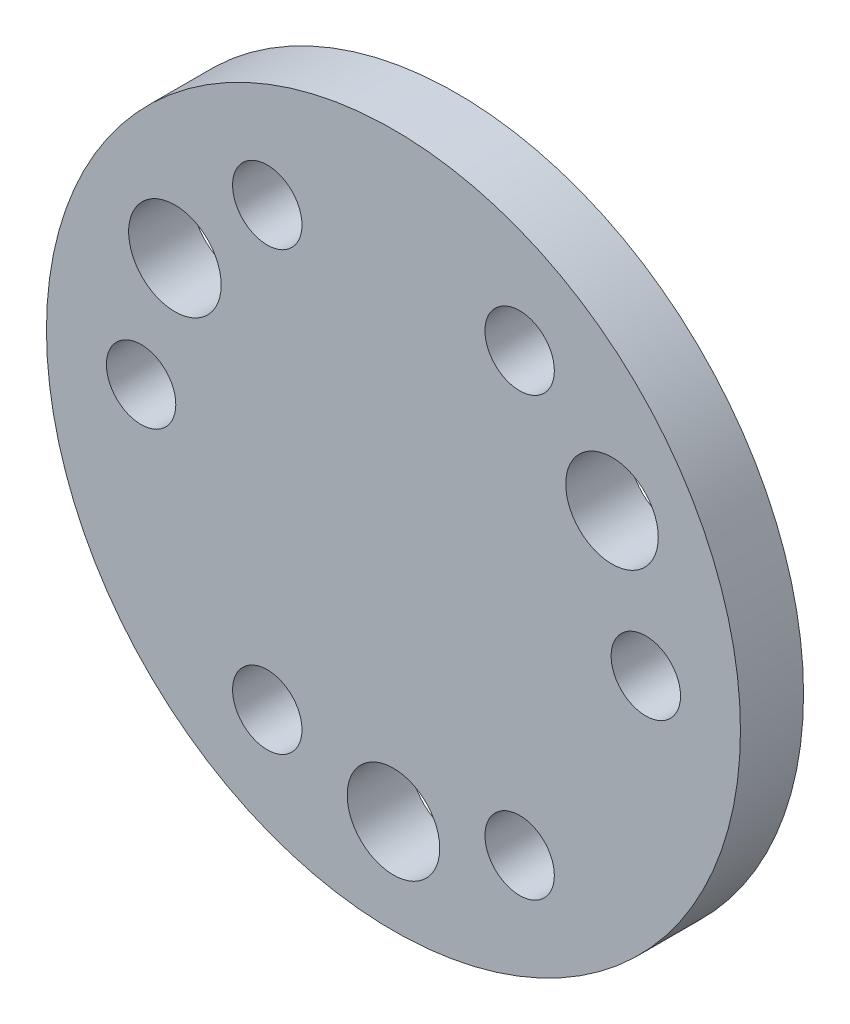
SolidWorks part; units mm, degrees
ref_plane "前视基准面" through (0, 0, 0) normal (0, 0, 1) x (1, 0, 0)
ref_plane "上视基准面" through (0, 0, 0) normal (0, 1, 0) x (1, 0, 0)
ref_plane "右视基准面" through (0, 0, 0) normal (1, 0, 0) x (0, 0, -1)
other "Configuration Table"
sketch "草图2" plane through (0, 0, 0) normal (0, 0, 1) x (1, 0, 0)
  circle A0 centre (0, 0) radius 16.5
  circle A1 centre (-10.3923, 6) radius 2.2
  circle A2 centre (-6, 10.3923) radius 1.65
  circle A3 centre (-12, 0) radius 1.65
  circle A4 centre (6, 10.3923) radius 1.65
  circle A5 centre (10.3923, 6) radius 2.2
  circle A6 centre (12, 0) radius 1.65
  circle A7 centre (6, -10.3923) radius 1.65
  circle A8 centre (0, -12) radius 2.2
  circle A9 centre (-6, -10.3923) radius 1.65
  point P27 (0, 0)
  dimension "D1" = 33
  dimension "D2" = 4.4
  dimension "D3" = 3.3
  dimension "D4" = 3
extrude "凸台-拉伸1" add sketch "草图2" along normal blind 3
